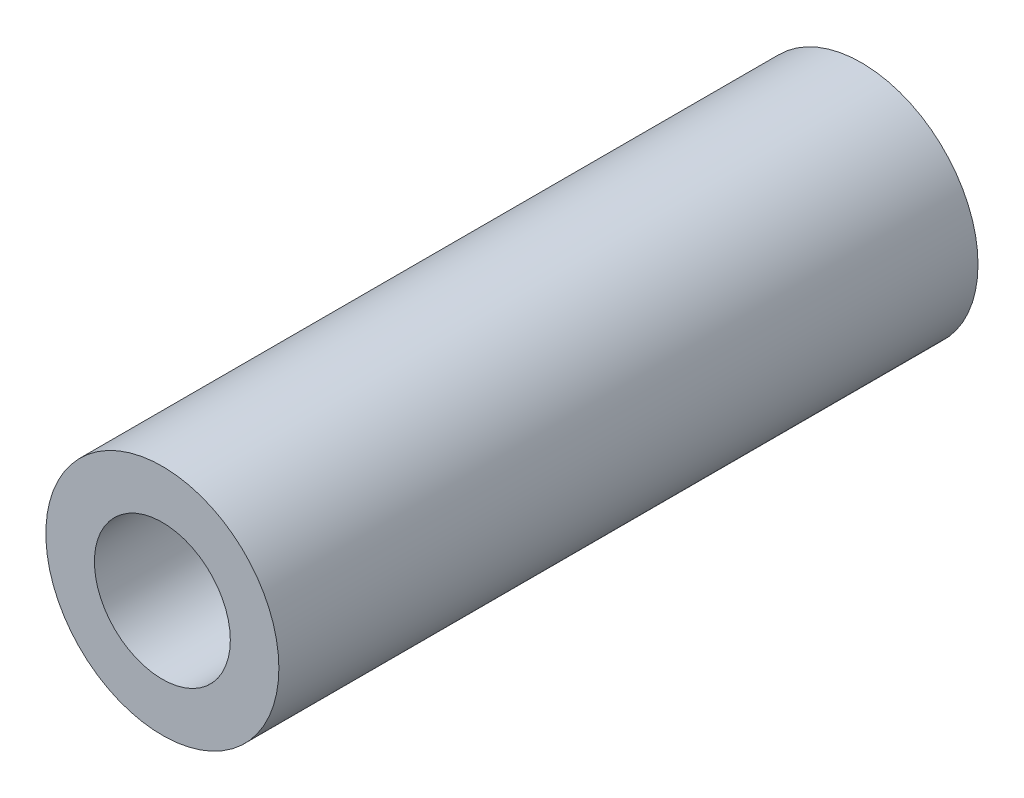
SolidWorks part; units mm, degrees
ref_plane "Piano frontale" through (0, 0, 0) normal (0, 0, 1) x (1, 0, 0)
ref_plane "Piano superiore" through (0, 0, 0) normal (0, 1, 0) x (1, 0, 0)
ref_plane "Piano destro" through (0, 0, 0) normal (1, 0, 0) x (0, 0, -1)
sketch "Schizzo1" plane through (0, 0, 0) normal (0, 0, 1) x (1, 0, 0)
  circle A0 centre (0, 0) radius 1.75
  circle A1 centre (0, 0) radius 3
  dimension "D1" = 3.5
  dimension "D2" = 6
extrude "Estrusione-Estrusione1" add sketch "Schizzo1" along normal blind 18
